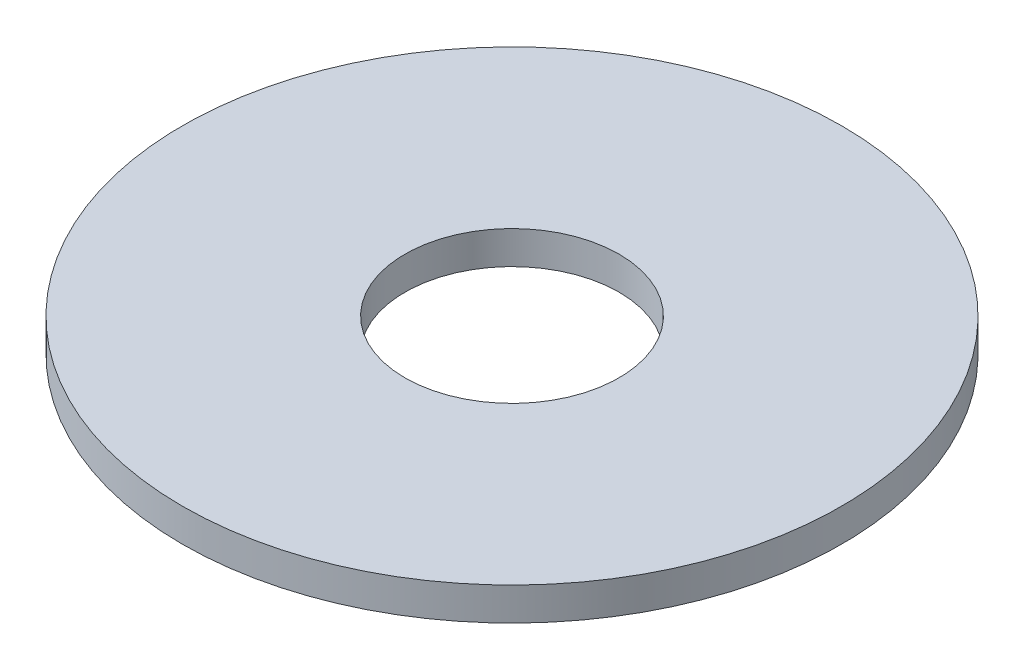
SolidWorks part; units mm, degrees
ref_plane "Спереди" through (0, 0, 0) normal (0, 0, 1) x (1, 0, 0)
ref_plane "Сверху" through (0, 0, 0) normal (0, 1, 0) x (1, 0, 0)
ref_plane "Справа" through (0, 0, 0) normal (1, 0, 0) x (0, 0, -1)
sketch "Эскиз1" plane through (0, 0, 0) normal (0, 1, 0) x (1, 0, 0)
  circle A0 centre (0, 0) radius 10
  circle A1 centre (0, 0) radius 3.25
  dimension "D1" = 20
  dimension "D2" = 6.5
extrude "Бобышка-Вытянуть1" add sketch "Эскиз1" along normal blind 1
